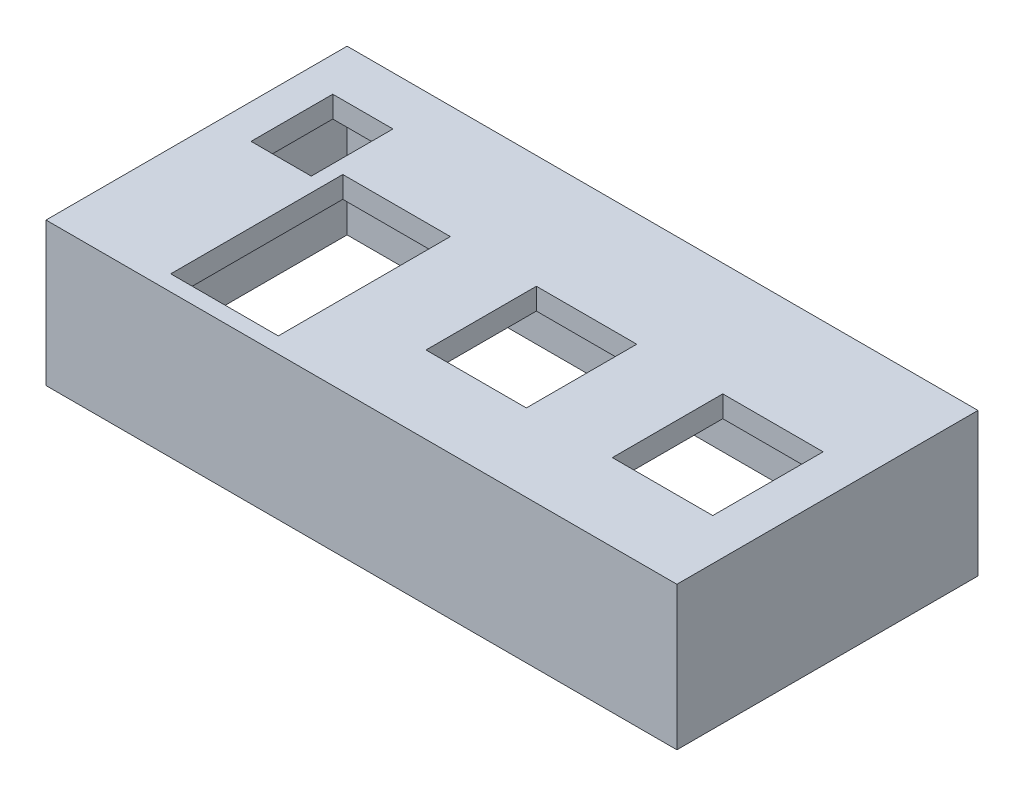
SolidWorks part; units mm, degrees
ref_plane "Plan de face" through (0, 0, 0) normal (0, 0, 1) x (1, 0, 0)
ref_plane "Plan de dessus" through (0, 0, 0) normal (0, 1, 0) x (1, 0, 0)
ref_plane "Plan de droite" through (0, 0, 0) normal (1, 0, 0) x (0, 0, -1)
sketch "Esquisse1" plane through (0, 0, 0) normal (0, 1, 0) x (1, 0, 0)
  line L1 (-69.6031, -0.5904) -> (18.3969, -0.5904)
  line L2 (-69.6031, -0.5904) -> (-69.6031, -42.5904)
  line L3 (-69.6031, -42.5904) -> (18.3969, -42.5904)
  line L4 (18.3969, -0.5904) -> (18.3969, -42.5904)
  dimension "D1" = 42
  dimension "D2" = 88
extrude "Boss.-Extru.1" add sketch "Esquisse1" along normal blind 20
sketch "Esquisse2" plane through (0, 0, 0) normal (0, 1, 0) x (1, 0, 0)
  line L0 (18.3969, -0.5904) -> (-69.6031, -0.5904) construction
  line L1 (-66.8031, -3.3904) -> (15.5969, -3.3904)
  line L2 (-66.8031, -3.3904) -> (-66.8031, -39.7904)
  line L3 (-66.8031, -39.7904) -> (15.5969, -39.7904)
  line L4 (15.5969, -3.3904) -> (15.5969, -39.7904)
  line L5 (-69.6031, -0.5904) -> (-69.6031, -42.5904) construction
  line L6 (-69.6031, -42.5904) -> (18.3969, -42.5904) construction
  line L7 (18.3969, -42.5904) -> (18.3969, -0.5904) construction
  point P8 (-69.6031, -21.5904)
  dimension "D1" = 2.8
  dimension "D2" = 2.8
  dimension "D3" = 2.8
  dimension "D4" = 2.8
extrude "Enlèv. mat.-Extru.1" cut sketch "Esquisse2" along normal blind 17
sketch "Esquisse3" plane through (0, 0, 0) normal (0, 1, 0) x (1, 0, 0)
  line L0 (-66.8031, -39.7904) -> (15.5969, -39.7904) construction
  line L1 (-1.4031, -31.7904) -> (12.5969, -31.7904)
  line L2 (-1.4031, -31.7904) -> (-1.4031, -16.3904)
  line L3 (-1.4031, -16.3904) -> (12.5969, -16.3904)
  line L4 (12.5969, -31.7904) -> (12.5969, -16.3904)
  line L5 (-27.4031, -31.7904) -> (-13.4031, -31.7904)
  line L6 (-27.4031, -31.7904) -> (-27.4031, -16.3904)
  line L7 (-27.4031, -16.3904) -> (-13.4031, -16.3904)
  line L8 (-13.4031, -31.7904) -> (-13.4031, -16.3904)
  line L9 (-54.4031, -40.3904) -> (-39.4031, -40.3904)
  line L10 (-54.4031, -40.3904) -> (-54.4031, -16.3904)
  line L11 (-54.4031, -16.3904) -> (-39.4031, -16.3904)
  line L12 (-39.4031, -40.3904) -> (-39.4031, -16.3904)
  line L13 (-64.8031, -18.7904) -> (-56.4031, -18.7904)
  line L14 (-64.8031, -18.7904) -> (-64.8031, -7.3904)
  line L15 (-64.8031, -7.3904) -> (-56.4031, -7.3904)
  line L16 (-56.4031, -18.7904) -> (-56.4031, -7.3904)
  line L17 (15.5969, -39.7904) -> (15.5969, -3.3904) construction
  line L19 (15.5969, -3.3904) -> (-66.8031, -3.3904) construction
  line L20 (15.5969, -3.3904) -> (-66.8031, -3.3904) construction
  line L21 (-66.8031, -39.7904) -> (15.5969, -39.7904) construction
  line L22 (-66.8031, -3.3904) -> (-66.8031, -39.7904) construction
  dimension "D1" = 8
  dimension "D2" = 3
  dimension "D3" = 13
  dimension "D4" = 14
  dimension "D5" = 8
  dimension "D6" = 13
  dimension "D7" = 12
  dimension "D8" = 14
  dimension "D9" = 12
  dimension "D10" = 13
  dimension "D11" = 24
  dimension "D12" = 15
  dimension "D13" = 4
  dimension "D14" = 21
  dimension "D15" = 2
  dimension "D16" = 2
extrude "Enlèv. mat.-Extru.3" cut sketch "Esquisse3" along normal blind 53
